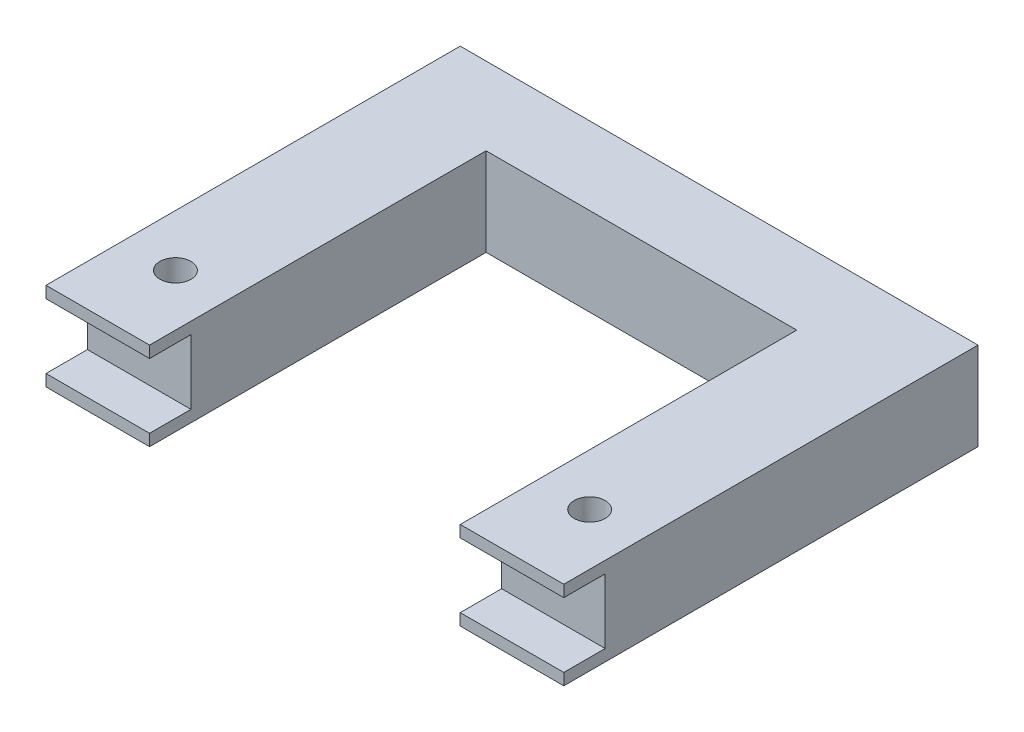
SolidWorks part; units mm, degrees
ref_plane "Alzado" through (0, 0, 0) normal (0, 0, 1) x (1, 0, 0)
ref_plane "Planta" through (0, 0, 0) normal (0, 1, 0) x (1, 0, 0)
ref_plane "Vista lateral" through (0, 0, 0) normal (1, 0, 0) x (0, 0, -1)
sketch "Croquis1" plane through (0, 0, 0) normal (0, 1, 0) x (1, 0, 0)
  line L0 (0, 0) -> (-20, 0)
  line L1 (-20, 0) -> (-20, 80)
  line L2 (-20, 80) -> (80, 80)
  line L3 (80, 80) -> (80, 0)
  line L4 (80, 0) -> (60, 0)
  line L5 (60, 0) -> (60, 65)
  line L6 (60, 65) -> (0, 65)
  line L7 (0, 65) -> (0, 0)
  dimension "D1" = 20
  dimension "D3" = 20
  dimension "D4" = 65
  dimension "D5" = 15
extrude "Saliente-Extruir1" add sketch "Croquis1" along normal blind 17
sketch "Croquis2" plane through (0, 0, 0) normal (0, 0, 1) x (1, 0, 0)
  line L0 (-20, 17) -> (-20, 0) construction
  line L1 (-20, 14.75) -> (80, 14.75)
  line L2 (-20, 14.75) -> (-20, 2.25)
  line L3 (-20, 2.25) -> (80, 2.25)
  line L4 (80, 14.75) -> (80, 2.25)
  line L5 (80, 17) -> (80, 0) construction
  line L6 (-20, 0) -> (0, 0) construction
  dimension "D1" = 12.5
  dimension "D2" = 2.25
extrude "Cortar-Extruir1" cut sketch "Croquis2" against normal blind 8
sketch "Croquis3" plane through (0, 17, 0) normal (0, 1, 0) x (1, 0, 0)
  line L0 (-10, 0) -> (-10, 15) construction
  line L1 (-20, 0) -> (0, 0) construction
  line L2 (70, 0) -> (70, 15) construction
  line L3 (60, 0) -> (80, 0) construction
  circle A0 centre (-10, 15) radius 3
  circle A1 centre (70, 15) radius 3
  dimension "D1" = 6
  dimension "D2" = 6
  dimension "D3" = 15
  dimension "D4" = 15
extrude "Cortar-Extruir2" cut sketch "Croquis3" against normal up to surface (17 mm away) up to face at (30, 0, -36.25)
